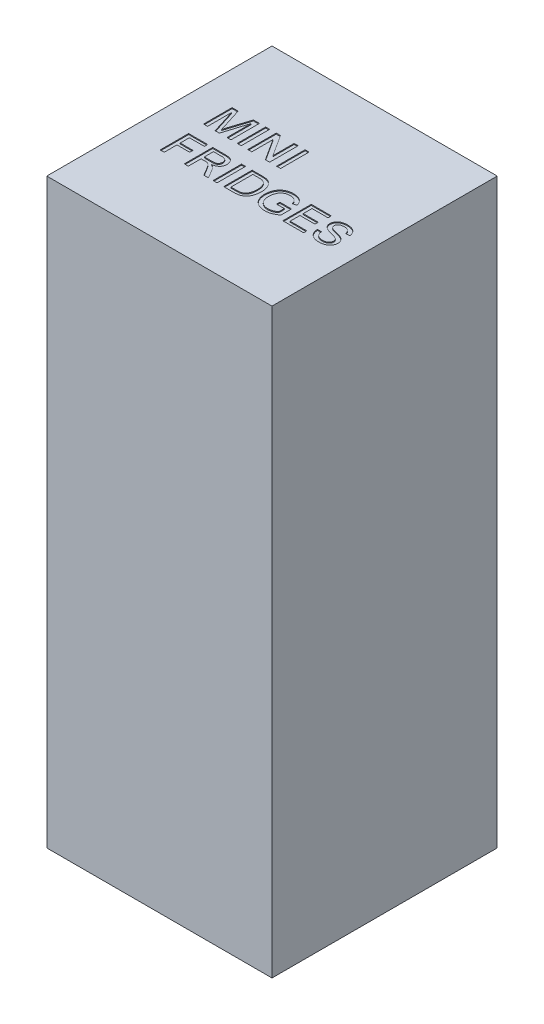
SolidWorks part; units mm, degrees
ref_plane "Front" through (0, 0, 0) normal (0, 0, 1) x (1, 0, 0)
ref_plane "Top" through (0, 0, 0) normal (0, 1, 0) x (1, 0, 0)
ref_plane "Right" through (0, 0, 0) normal (1, 0, 0) x (0, 0, -1)
sketch "Sketch1" plane through (0, 0, 0) normal (0, 1, 0) x (1, 0, 0)
  line L1 (-304.8, 304.8) -> (304.8, 304.8)
  line L2 (-304.8, 304.8) -> (-304.8, -304.8)
  line L3 (-304.8, -304.8) -> (304.8, -304.8)
  line L4 (304.8, 304.8) -> (304.8, -304.8)
  line L5 (-304.8, 304.8) -> (304.8, -304.8) construction
  line L6 (-304.8, -304.8) -> (304.8, 304.8) construction
  point P0 (0, 0)
  dimension "D1" = 609.6
  dimension "D2" = 609.6
extrude "Boss-Extrude1" add sketch "Sketch1" along normal blind 1574.8
sketch "Sketch2" plane through (0, 1574.8, 0) normal (0, 1, 0) x (1, 0, 0)
  line L0 (-221.404, 29.3712) -> (221.9634, 29.3712) construction
  text T0 "MINI \r\nFRIDGES" font "Arial" height in points 300
extrude "Cut-Extrude1" cut sketch "Sketch2" against normal blind 2.54
